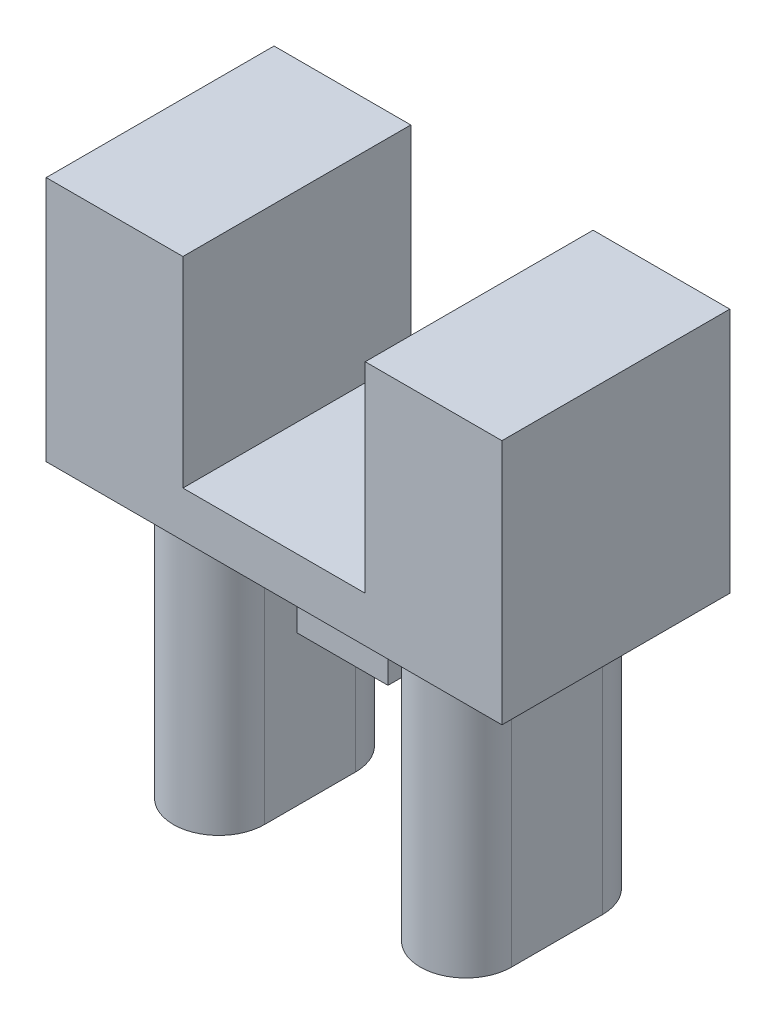
SolidWorks part; units mm, degrees
ref_plane "Front Plane" through (0, 0, 0) normal (0, 0, 1) x (1, 0, 0)
ref_plane "Top Plane" through (0, 0, 0) normal (0, 1, 0) x (1, 0, 0)
ref_plane "Right Plane" through (0, 0, 0) normal (1, 0, 0) x (0, 0, -1)
sketch "Sketch1" plane through (0, 0, 0) normal (0, 0, 1) x (1, 0, 0)
  line L0 (0, 0) -> (0, 11.8596) construction
  line L1 (6.35, -3.429) -> (-6.35, -3.429)
  line L2 (6.35, -3.429) -> (6.35, 3.429)
  line L3 (6.35, 3.429) -> (2.54, 3.429)
  line L4 (-6.35, -3.429) -> (-6.35, 3.429)
  line L5 (6.35, -3.429) -> (-6.35, 3.429) construction
  line L6 (6.35, 3.429) -> (-6.35, -3.429) construction
  line L7 (-2.54, 3.429) -> (-6.35, 3.429)
  line L8 (2.54, -2.159) -> (-2.54, -2.159)
  line L9 (2.54, -2.159) -> (2.54, 3.429)
  line L11 (-2.54, -2.159) -> (-2.54, 3.429)
  line L12 (2.54, -2.159) -> (-2.54, 3.429) construction
  line L13 (2.54, 3.429) -> (-2.54, -2.159) construction
  point P0 (0, 0)
  point P8 (0, 0.635)
  dimension "D1" = 12.7
  dimension "D2" = 6.858
  dimension "D3" = 5.08
  dimension "D4" = 5.588
extrude "Boss-Extrude1" add sketch "Sketch1" along normal blind 6.35
sketch "Sketch2" plane through (0, -3.429, 0) normal (0, -1, 0) x (1, 0, 0)
  line L0 (-6.35, 6.35) -> (6.35, 0) construction
  line L2 (-1.27, 1.905) -> (1.27, 1.905)
  line L3 (-1.27, 1.905) -> (-1.27, 4.445)
  line L4 (-1.27, 4.445) -> (1.27, 4.445)
  line L5 (1.27, 1.905) -> (1.27, 4.445)
  line L6 (-1.27, 1.905) -> (1.27, 4.445) construction
  line L7 (-1.27, 4.445) -> (1.27, 1.905) construction
  point P4 (0, 3.175)
  dimension "D1" = 2.54
  dimension "D2" = 2.54
extrude "Boss-Extrude2" add sketch "Sketch2" along normal blind 2.54
sketch "Sketch3" plane through (0, -3.429, 0) normal (0, -1, 0) x (1, 0, 0)
  line L0 (-6.35, 6.35) -> (6.35, 0) construction
  line L1 (-6.35, 6.35) -> (-6.35, 0) construction
  line L2 (0, 3.175) -> (-8.5215, 3.175) construction
  line L3 (-3.4411, 1.905) -> (-3.4411, 4.445) construction
  line L4 (-4.7111, 1.905) -> (-4.7111, 4.445)
  line L5 (-2.1711, 1.905) -> (-2.1711, 4.445)
  line L6 (0, 3.175) -> (0, 7.1298) construction
  line L7 (3.4411, 1.905) -> (3.4411, 4.445) construction
  line L8 (4.7111, 1.905) -> (4.7111, 4.445)
  line L9 (2.1711, 1.905) -> (2.1711, 4.445)
  arc A0 (-4.7111, 1.905) -> (-2.1711, 1.905) centre (-3.4411, 1.905) ccw
  arc A1 (-2.1711, 4.445) -> (-4.7111, 4.445) centre (-3.4411, 4.445) ccw
  arc A2 (4.7111, 1.905) -> (2.1711, 1.905) centre (3.4411, 1.905) cw
  arc A3 (2.1711, 4.445) -> (4.7111, 4.445) centre (3.4411, 4.445) cw
  point P9 (-3.4411, 3.175)
  point P18 (3.4411, 3.175)
  dimension "D1" = 1.27
  dimension "D2" = 2.54
extrude "Boss-Extrude3" add sketch "Sketch3" along normal blind 7.62
ref_plane "Midplane" through (0, 0, 0) normal (1, 0, 0) x (0, 0, -1)
ref_plane "Plane2" through (0, 0, 3.175) normal (0, 0, 1) x (1, 0, 0)
